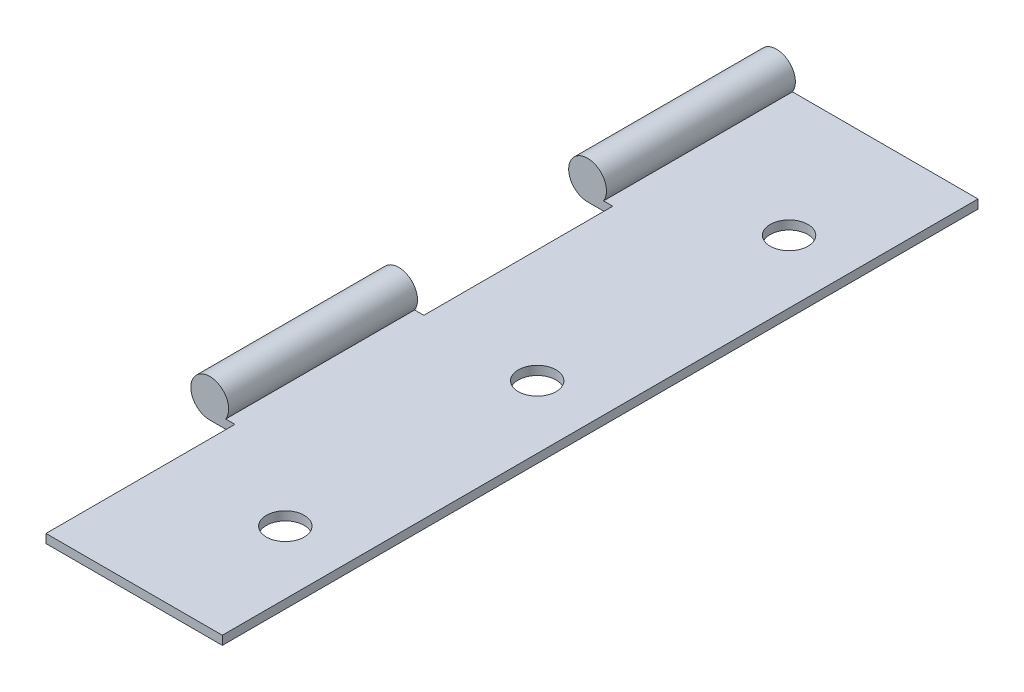
SolidWorks part; units mm, degrees
ref_plane "Plan de face" through (0, 0, 0) normal (0, 0, 1) x (1, 0, 0)
ref_plane "Plan de dessus" through (0, 0, 0) normal (0, 1, 0) x (1, 0, 0)
ref_plane "Plan de droite" through (0, 0, 0) normal (1, 0, 0) x (0, 0, -1)
sketch "Esquisse1" plane through (0, 0, 0) normal (0, 0, 1) x (1, 0, 0)
  line L1 (0, 0) -> (16, 0)
  line L3 (1.2689, 0.7) -> (16, 0.7)
  line L4 (16, 0) -> (16, 0.7)
  arc A0 (1.2689, 0.7) -> (0, 0) centre (0, 1.5) ccw
  dimension "D1" = 16
  dimension "D2" = 3
  dimension "D3" = 0.7
extrude "Extrusion1" add sketch "Esquisse1" along normal blind 60
sketch "Esquisse2" plane through (0, 0.7, 0) normal (0, 1, 0) x (1, 0, 0)
  line L0 (16, -60) -> (1.2689, -60) construction
  line L1 (16, -60) -> (16, 0) construction
  line L2 (2, -60) -> (-5.047, -60)
  line L3 (2, -60) -> (2, -45)
  line L4 (2, -45) -> (-5.047, -45)
  line L5 (-5.047, -60) -> (-5.047, -45)
  dimension "D1" = 14
  dimension "D2" = 15
extrude "Extrusion2" cut sketch "Esquisse2" along normal through all from offset 10
pattern_linear "Répétition linéaire1" count 2 spacing 30 along (0, 0, -1) of "Extrusion2"
sketch "Esquisse3" plane through (0, 0.7, 0) normal (0, 1, 0) x (1, 0, 0)
  line L0 (16, -60) -> (16, 0) construction
  line L1 (16, -60) -> (2, -60) construction
  circle A0 centre (11, -50) radius 1.5
  dimension "D1" = 3
  dimension "D2" = 5
  dimension "D3" = 10
extrude "Extrusion3" cut sketch "Esquisse3" against normal through all
pattern_linear "Répétition linéaire2" count 3 spacing 20 along (0, 0, -1) of "Extrusion3"
